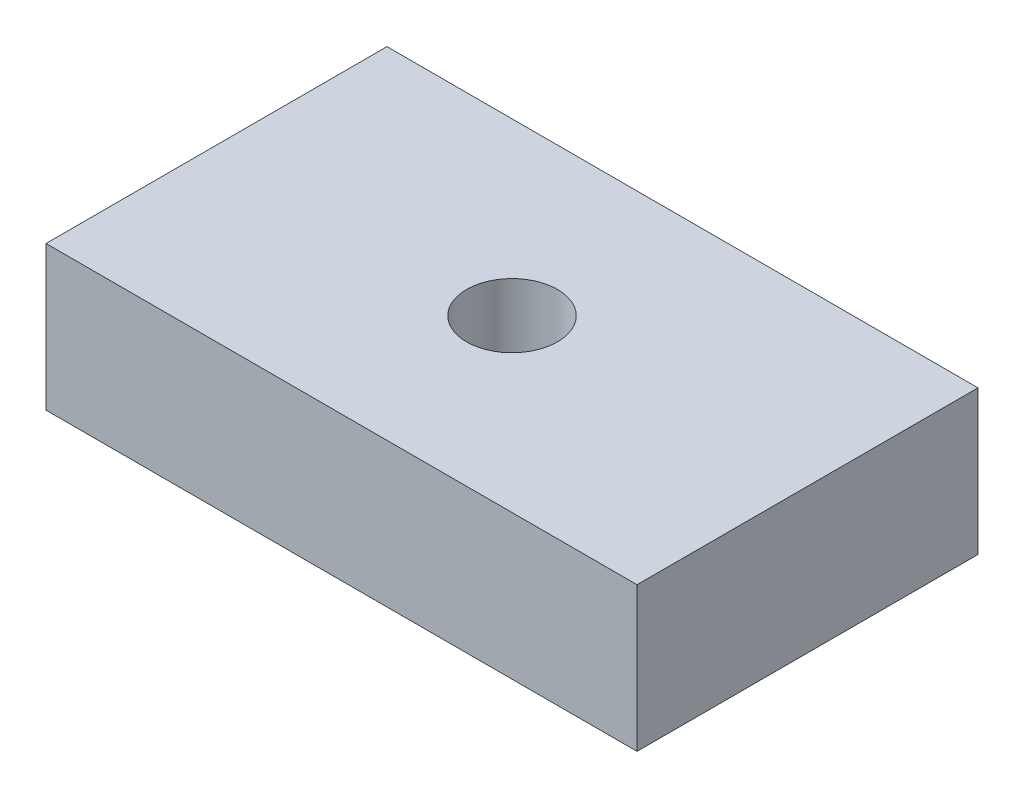
SolidWorks part; units mm, degrees
ref_plane "Alzado" through (0, 0, 0) normal (0, 0, 1) x (1, 0, 0)
ref_plane "Planta" through (0, 0, 0) normal (0, 1, 0) x (1, 0, 0)
ref_plane "Vista lateral" through (0, 0, 0) normal (1, 0, 0) x (0, 0, -1)
sketch "Sketch1" plane through (0, 0, 0) normal (0, 1, 0) x (1, 0, 0)
  line L1 (-26, -7.5) -> (26, -7.5)
  line L2 (-26, -7.5) -> (-26, 7.5)
  line L3 (-26, 7.5) -> (26, 7.5)
  line L4 (26, -7.5) -> (26, 7.5)
  line L5 (-26, -7.5) -> (26, 7.5) construction
  line L6 (-26, 7.5) -> (26, -7.5) construction
  point P0 (0, 0)
  dimension "D1" = 52
  dimension "D2" = 15
extrude "Boss-Extrude1" add sketch "Sketch1" along normal blind 6.35
sketch "Sketch3" plane through (0, 6.35, 0) normal (0, 1, 0) x (1, 0, 0)
  line L0 (-26, 0) -> (26, 0) construction
  line L1 (26, -7.5) -> (26, 7.5) construction
  line L2 (-26, 0) -> (0, 0) construction
  line L3 (-13, 0) -> (13, 0) construction
  circle A0 centre (-13, 0) radius 2
  circle A1 centre (13, 0) radius 2
  point P6 (0, 0)
  point P16 (0, 0)
  dimension "D1" = 4
  dimension "D2" = 4
  dimension "D3" = 13
extrude "Cut-Extrude2" cut sketch "Sketch3" against normal through all
sketch "Sketch2" plane through (0, 6.35, 0) normal (0, 1, 0) x (1, 0, 0)
  line L0 (-26, -7.5) -> (26, -7.5) construction
  line L1 (26, 7.5) -> (0, 7.5)
  line L2 (26, 7.5) -> (26, -7.5)
  line L3 (26, -7.5) -> (0, -7.5)
  line L4 (0, 7.5) -> (0, -7.5)
  line L5 (26, 7.5) -> (0, -7.5) construction
  line L6 (26, -7.5) -> (0, 7.5) construction
  point P4 (13, 0)
extrude "Cut-Extrude1" cut sketch "Sketch2" against normal through all
